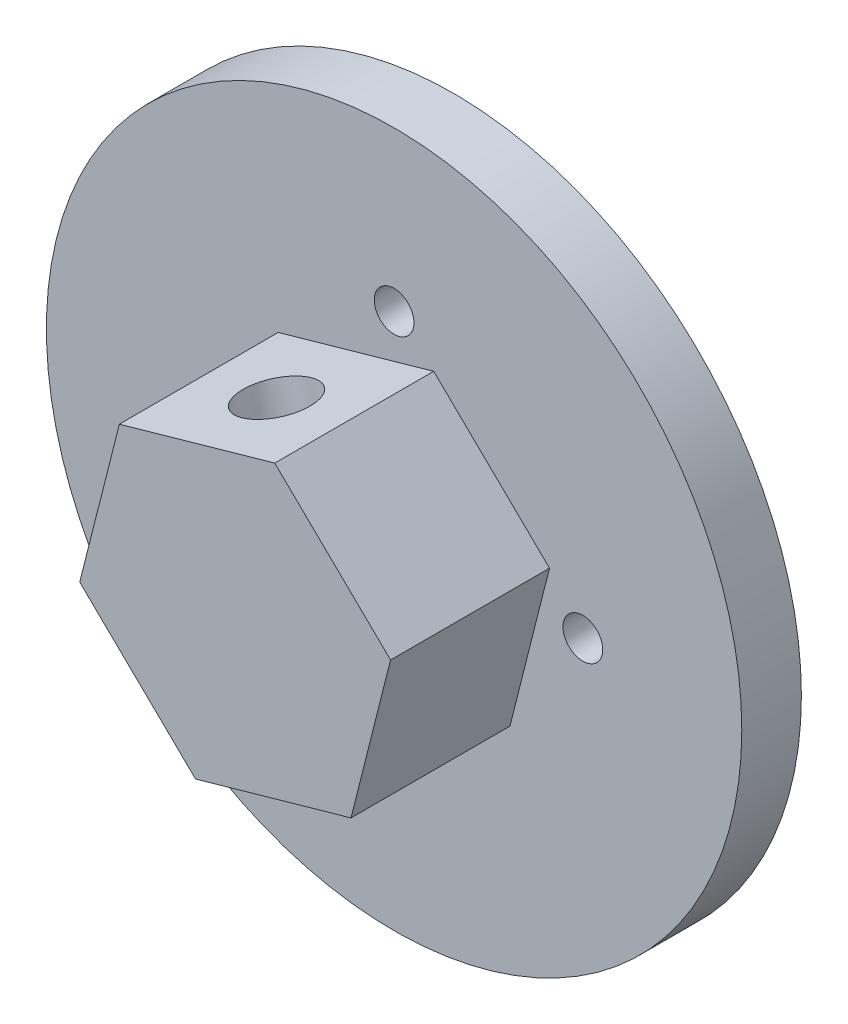
SolidWorks part; units mm, degrees
ref_plane "Alzado" through (0, 0, 0) normal (0, 0, 1) x (1, 0, 0)
ref_plane "Planta" through (0, 0, 0) normal (0, 1, 0) x (1, 0, 0)
ref_plane "Vista lateral" through (0, 0, 0) normal (1, 0, 0) x (0, 0, -1)
sketch "Croquis1" plane through (0, 0, 0) normal (0, 0, 1) x (1, 0, 0)
  circle A0 centre (0, 0) radius 17.5
  circle A1 centre (0, 0) radius 9.5 construction
  circle A2 centre (0, 9.5) radius 1
  circle A3 centre (9.5, 0) radius 1
  circle A4 centre (0, -9.5) radius 1
  circle A5 centre (-9.5, 0) radius 1
  point P15 (0, 0)
  dimension "D1" = 35
  dimension "D2" = 19
  dimension "D3" = 2
  dimension "D4" = 4
extrude "Saliente-Extruir1" add sketch "Croquis1" along normal blind 3
sketch "Croquis2" plane through (0, 0, 3) normal (0, 0, 1) x (1, 0, 0)
  line L1 (1.9936, 7.8818) -> (-5.8291, 5.6674)
  line L2 (-5.8291, 5.6674) -> (-7.8226, -2.2144)
  line L3 (-7.8226, -2.2144) -> (-1.9936, -7.8818)
  line L4 (-1.9936, -7.8818) -> (5.8291, -5.6674)
  line L5 (5.8291, -5.6674) -> (7.8226, 2.2144)
  line L6 (7.8226, 2.2144) -> (1.9936, 7.8818)
  circle A0 centre (0, 0) radius 7.0408 construction
  circle A1 centre (0, 9.5) radius 2.1 construction
  circle A2 centre (9.5, 0) radius 2.1 construction
  circle A3 centre (0, -9.5) radius 2.1 construction
  circle A4 centre (-9.5, 0) radius 2.1 construction
  point P21 (0, 0)
  dimension "D1" = 4.2
  dimension "D2" = 4
extrude "Saliente-Extruir2" add sketch "Croquis2" along normal blind 8
sketch "Croquis3" plane through (1.9177, -6.7746, 0) normal (0.2724, -0.9622, 0) x (0.9622, 0.2724, 0)
  circle A0 centre (0, 7) radius 1.75
extrude "Cortar-Extruir1" cut sketch "Croquis3" against normal up to next
